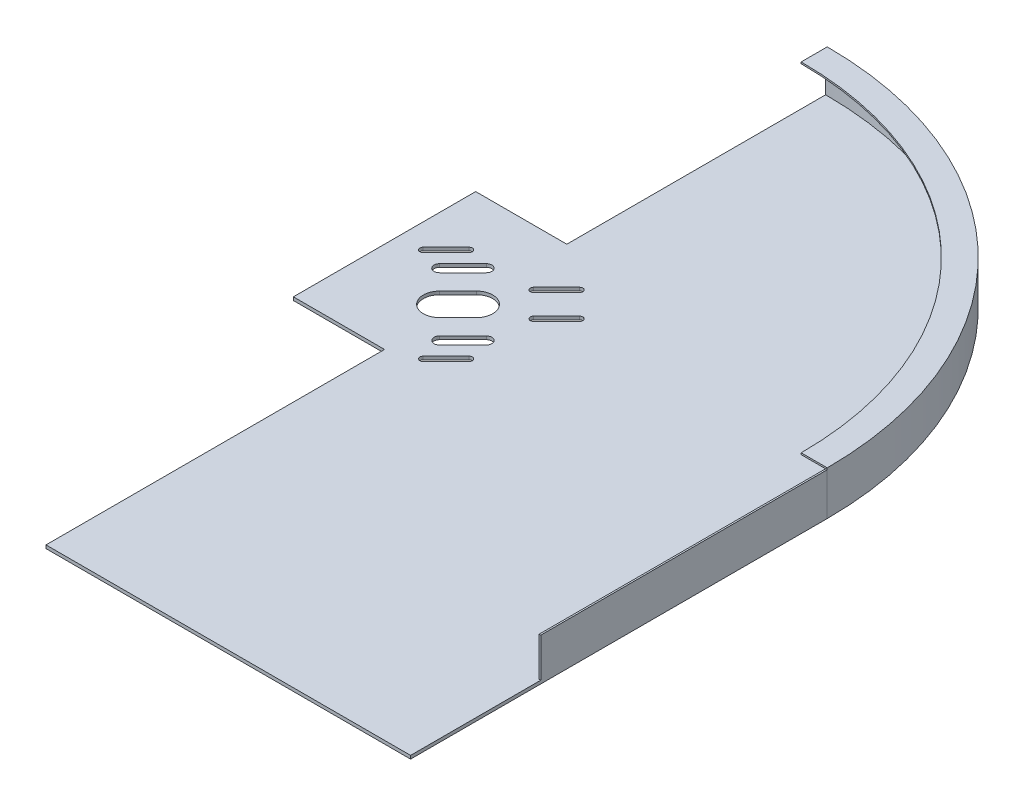
SolidWorks part; units mm, degrees
ref_plane "Front Plane" through (0, 0, 0) normal (0, 0, 1) x (1, 0, 0)
ref_plane "Top Plane" through (0, 0, 0) normal (0, 1, 0) x (1, 0, 0)
ref_plane "Right Plane" through (0, 0, 0) normal (1, 0, 0) x (0, 0, -1)
sketch "Sketch2" plane through (0, 0, 0) normal (0, 1, 0) x (1, 0, 0)
  line L0 (0, 355.6) -> (0, 0)
  line L1 (0, 0) -> (0, -304.8)
  line L2 (355.6, 0) -> (355.6, -304.8)
  line L3 (0, -304.8) -> (355.6, -304.8)
  arc A0 (0, 355.6) -> (355.6, 0) centre (0, 0) cw
  dimension "D1" = 304.8
  dimension "D2" = 355.6
extrude "Boss-Extrude1" add sketch "Sketch2" along normal blind 3.175
sketch "Sketch3" plane through (0, 3.175, 0) normal (0, 1, 0) x (1, 0, 0)
  line L0 (355.6, -304.8) -> (355.6, 0) construction
  line L1 (0, 355.6) -> (0, -304.8) construction
  line L2 (0, 355.6) -> (0, 354.0125)
  line L3 (354.0125, 0) -> (355.6, 0)
  arc A0 (0, 355.6) -> (355.6, 0) centre (0, 0) cw
  arc A1 (0, 354.0125) -> (354.0125, 0) centre (0, 0) cw
  dimension "D1" = 1.5875
extrude "Boss-Extrude2" add sketch "Sketch3" along normal blind 38.1
sketch "Sketch4" plane through (0, 3.175, 0) normal (0, 1, 0) x (1, 0, 0)
  line L0 (354.0125, -279.4) -> (355.6, -279.4)
  line L1 (354.0125, 0) -> (355.6, 0)
  line L2 (354.0125, 0) -> (354.0125, -304.8)
  line L3 (354.0125, -304.8) -> (355.6, -304.8)
  line L4 (355.6, 0) -> (355.6, -304.8)
  line M1 (355.6, 0) -> (354.0125, 0)
  line M5 (355.6, -304.8) -> (355.6, 0)
  dimension "D1" = 279.4
extrude "Boss-Extrude3" add sketch "Sketch4" along normal blind 38.1 contours L2 L0 M1 M5
sketch "Sketch6" plane through (0, 3.175, 0) normal (0, 1, 0) x (1, 0, 0)
  circle A0 centre (0, 0) radius 1.5875
extrude "Cut-Extrude1" cut sketch "Sketch6" against normal blind 19.05
sketch "Sketch10" plane through (0, 0, 0) normal (-1, 0, 0) x (0, 0, 1)
  line L0 (-354.0125, 3.175) -> (-1.5875, 3.175) construction
  line L1 (-38.1, 3.175) -> (63.5, 3.175)
  line L2 (-38.1, 3.175) -> (-38.1, 0)
  line L3 (-38.1, 0) -> (63.5, 0)
  line L4 (63.5, 3.175) -> (63.5, 0)
  line L5 (1.5875, 0) -> (304.8, 0) construction
  dimension "D1" = 101.6
  dimension "D2" = 38.1
extrude "Boss-Extrude5" add sketch "Sketch10" along normal blind 63.5
sketch "Sketch12" plane through (0, 0, 0) normal (0, -1, 0) x (1, 0, 0)
  line L0 (0, 304.8) -> (355.6, 304.8) construction
  line L1 (0, 304.8) -> (355.6, 304.8)
  line L2 (0, 304.8) -> (0, 406.4)
  line L3 (0, 406.4) -> (355.6, 406.4)
  line L4 (355.6, 304.8) -> (355.6, 406.4)
  line L5 (355.6, 304.8) -> (355.6, 0) construction
  dimension "D1" = 101.6
extrude "Boss-Extrude6" add sketch "Sketch12" against normal blind 3.175
sketch "Sketch13" plane through (0, 3.175, 0) normal (0, 1, 0) x (1, 0, 0)
  line L0 (0, 354.0125) -> (0, 38.1) construction
  line L1 (-63.5, 38.1) -> (0, 38.1)
  line L2 (-63.5, 38.1) -> (-63.5, 101.6)
  line L3 (-63.5, 101.6) -> (0, 101.6)
  line L4 (0, 38.1) -> (0, 101.6)
  line L5 (-63.5, -63.5) -> (-63.5, 38.1) construction
  line L6 (-63.5, -63.5) -> (0, -63.5)
  line L7 (-63.5, -63.5) -> (-63.5, -76.2)
  line L8 (-63.5, -76.2) -> (0, -76.2)
  line L9 (0, -63.5) -> (0, -76.2)
  line L10 (0, -63.5) -> (0, -406.4) construction
  line L11 (-63.5, -63.5) -> (0, -63.5) construction
  dimension "D1" = 63.5
  dimension "D2" = 12.7
extrude "Boss-Extrude7" add sketch "Sketch13" against normal blind 3.175
sketch "Sketch14" plane through (0, 3.175, 0) normal (0, 1, 0) x (1, 0, 0)
  line L0 (0, 354.0125) -> (0, 101.6) construction
  line L1 (290.2348, 0) -> (215.5261, 0)
  line L2 (0, 303.2125) -> (0, 203.2)
  arc A0 (0, 303.2125) -> (302.9226, 13.2552) centre (0, 0) cw
  arc A1 (0, 203.2) -> (202.8481, 11.9529) centre (0, 0) cw
  arc A2 (354.0125, 0) -> (0, 354.0125) centre (0, 0) ccw construction
  arc A3 (202.8481, 11.9529) -> (215.5261, 0) centre (215.5261, 12.7) ccw
  arc A4 (290.2348, 0) -> (302.9226, 13.2552) centre (290.2348, 12.7) ccw
  dimension "D1" = 50.8
  dimension "D2" = 203.2
  dimension "D3" = 12.7
extrude "Cut-Extrude4" [suppressed] cut sketch "Sketch14" against normal blind 3.175
sketch "Sketch11" plane through (0, 3.175, 0) normal (0, 1, 0) x (1, 0, 0)
  line L0 (-11.2253, -11.2253) -> (6.7352, 6.7352) construction
  line L2 (-22.4506, 0) -> (-4.4901, 17.9605)
  line L3 (0, -22.4506) -> (17.9605, -4.4901)
  arc A0 (-22.4506, 0) -> (0, -22.4506) centre (-11.2253, -11.2253) ccw
  arc A1 (17.9605, -4.4901) -> (-4.4901, 17.9605) centre (6.7352, 6.7352) ccw
  point P4 (-2.2451, -2.2451)
  dimension "D1" = 25.4
  dimension "D2" = 15.875
extrude "Cut-Extrude3" cut sketch "Sketch11" against normal blind 38.1
sketch "Sketch17" plane through (0, 3.175, 0) normal (0, 1, 0) x (1, 0, 0)
  line L0 (17.9605, 17.9605) -> (-22.4506, -22.4506) construction
  line L1 (-12.9486, -12.9486) -> (-40.3384, 14.4412) construction
  arc A1 (17.9605, -4.4901) -> (-4.4901, 17.9605) centre (6.7352, 6.7352) ccw construction
  arc A2 (-22.4506, 0) -> (0, -22.4506) centre (-11.2253, -11.2253) ccw construction
  dimension "D1" = 18.3121
  dimension "D2" = 38.735
sketch "Sketch18" plane through (0, 41.275, 0) normal (0, 1, 0) x (1, 0, 0)
  line L0 (0, 355.6) -> (0, 330.2)
  line L1 (355.6, 0) -> (330.2, 0)
  arc A0 (0, 355.6) -> (355.6, 0) centre (0, 0) cw
  arc A1 (0, 330.2) -> (330.2, 0) centre (0, 0) cw
  dimension "D1" = 25.4
extrude "Boss-Extrude10" add sketch "Sketch18" along normal blind 1.5875
extrude "Cut-Extrude5" cut sketch "Sketch19" against normal blind 3.175
sketch "Sketch19" plane through (44.8661, 3.175, 35.3849) normal (0, 1, 0) x (-0.7071, 0, -0.7071)
  line L0 (13.566, 22.5792) -> (13.566, -9.5666) construction
  line L1 (19.0042, 22.5792) -> (19.0042, -9.5666)
  line L2 (8.1278, 22.5792) -> (8.1278, -9.5666)
  line L4 (56.746, 22.5792) -> (0.2127, 22.5792) construction
  line L5 (56.746, 22.5792) -> (56.746, -18.6958) construction
  line L6 (99.926, 22.5792) -> (99.926, -9.5666) construction
  line L7 (94.4735, 22.5792) -> (94.4735, -9.5666)
  line L8 (105.3786, 22.5792) -> (105.3786, -9.5666)
  line L9 (85.321, 59.0917) -> (56.746, 22.5792) construction
  line L13 (56.746, 22.5792) -> (56.746, 57.8082) construction
  line L14 (56.746, 22.5792) -> (99.926, 22.5792) construction
  arc A0 (94.4735, 22.5792) -> (105.3786, 22.5792) centre (99.926, 22.5792) cw
  arc A2 (19.0042, 22.5792) -> (8.1278, 22.5792) centre (13.566, 22.5792) ccw
  arc A3 (8.1278, -9.5666) -> (19.0042, -9.5666) centre (13.566, -9.5666) ccw
  arc A4 (105.3786, -9.5666) -> (94.4735, -9.5666) centre (99.926, -9.5666) cw
  point P4 (13.566, 6.5063)
  point P16 (99.926, 6.5063)
sketch "Sketch22" plane through (0, 0, 0) normal (0, -1, 0) x (1, 0, 0)
  line L0 (-63.5, 76.2) -> (0, 76.2) construction
  line L1 (-63.5, -101.6) -> (-88.9, -101.6)
  line L2 (-63.5, -101.6) -> (-63.5, 76.2)
  line L3 (-63.5, 76.2) -> (-88.9, 76.2)
  line L4 (-88.9, -101.6) -> (-88.9, 76.2)
  dimension "D1" = 25.4
extrude "Boss-Extrude11" add sketch "Sketch22" against normal blind 3.175
extrude "Cut-Extrude6" cut sketch "Sketch20" along normal blind 33.02
sketch "Sketch20" plane through (269.3999, -22.225, -80.4465) normal (0, 1, 0) x (1, 0, 0)
  line L0 (-334.7312, -53.7303) -> (-312.2806, -31.2796) construction
  line L1 (-336.9763, -51.4852) -> (-314.5256, -29.0346)
  line L2 (-332.4862, -55.9753) -> (-310.0355, -33.5247)
  line L3 (-247.0358, -33.6626) -> (-224.5852, -11.212) construction
  line L5 (-262.6647, -73.7113) -> (-296.9649, -108.0116) construction
  line L6 (-242.6836, -145.7779) -> (-220.233, -123.3273) construction
  line L7 (-240.4385, -148.023) -> (-217.9879, -125.5723)
  line L8 (-244.9287, -143.5328) -> (-222.478, -121.0822)
  line L9 (-249.2809, -31.4175) -> (-226.8302, -8.9669)
  line L10 (-244.7907, -35.9077) -> (-222.3401, -13.457)
  line L11 (-222.6159, -58.0825) -> (-200.1653, -35.6318) construction
  line L12 (-262.6647, -73.7113) -> (-233.8412, -44.8879) construction
  line L13 (-220.3709, -60.3276) -> (-197.9202, -37.8769)
  line L14 (-224.861, -55.8374) -> (-202.4104, -33.3868)
  arc A0 (-336.9763, -51.4852) -> (-332.4862, -55.9753) centre (-334.7312, -53.7303) ccw
  arc A1 (-310.0355, -33.5247) -> (-314.5256, -29.0346) centre (-312.2806, -31.2796) ccw
  arc A3 (-240.4385, -148.023) -> (-244.9287, -143.5328) centre (-242.6836, -145.7779) cw
  arc A4 (-222.478, -121.0822) -> (-217.9879, -125.5723) centre (-220.233, -123.3273) cw
  arc A5 (-249.2809, -31.4175) -> (-244.7907, -35.9077) centre (-247.0358, -33.6626) ccw
  arc A6 (-222.3401, -13.457) -> (-226.8302, -8.9669) centre (-224.5852, -11.212) ccw
  arc A8 (-220.3709, -60.3276) -> (-224.861, -55.8374) centre (-222.6159, -58.0825) cw
  arc A9 (-202.4104, -33.3868) -> (-197.9202, -37.8769) centre (-200.1653, -35.6318) cw
  point P2 (-323.5059, -42.505)
  point P16 (-231.4583, -134.5526)
  point P23 (-235.8105, -22.4373)
  point P33 (-211.3906, -46.8572)
